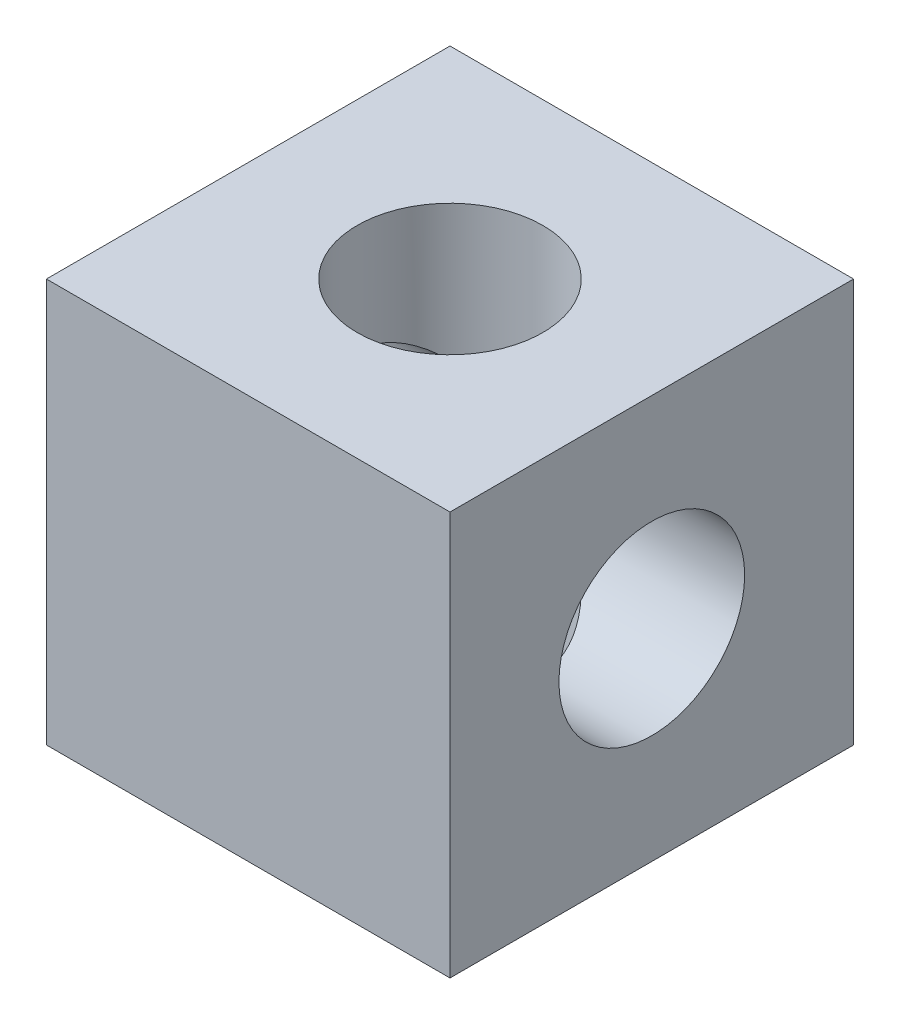
SolidWorks part; units mm, degrees
ref_plane "Ön Düzlem" through (0, 0, 0) normal (0, 0, 1) x (1, 0, 0)
ref_plane "Üst Düzlem" through (0, 0, 0) normal (0, 1, 0) x (1, 0, 0)
ref_plane "Sağ Düzlem" through (0, 0, 0) normal (1, 0, 0) x (0, 0, -1)
sketch "Çizim1" plane through (0, 0, 0) normal (0, 0, 1) x (1, 0, 0)
  line L1 (-12.699, 6.7248) -> (7.621, 6.7248)
  line L2 (-12.699, 6.7248) -> (-12.699, -13.5952)
  line L3 (-12.699, -13.5952) -> (7.621, -13.5952)
  line L4 (7.621, 6.7248) -> (7.621, -13.5952)
  dimension "D1" = 20.32
  dimension "D2" = 20.32
extrude "Yükseklik-Ekstrüzyon1" add sketch "Çizim1" along normal blind 20.32
sketch "Çizim2" plane through (0, 6.7248, 0) normal (0, 1, 0) x (1, 0, 0)
  circle A0 centre (-2.539, -10.16) radius 4.675
  dimension "D1" = 9.35
extrude "Kes-Ekstrüzyon1" cut sketch "Çizim2" against normal through all
sketch "Çizim3" plane through (-12.699, 0, 0) normal (-1, 0, 0) x (0, 0, 1)
  circle A0 centre (10.16, -3.4352) radius 4.675
  dimension "D1" = 9.35
extrude "Kes-Ekstrüzyon2" cut sketch "Çizim3" against normal through all
